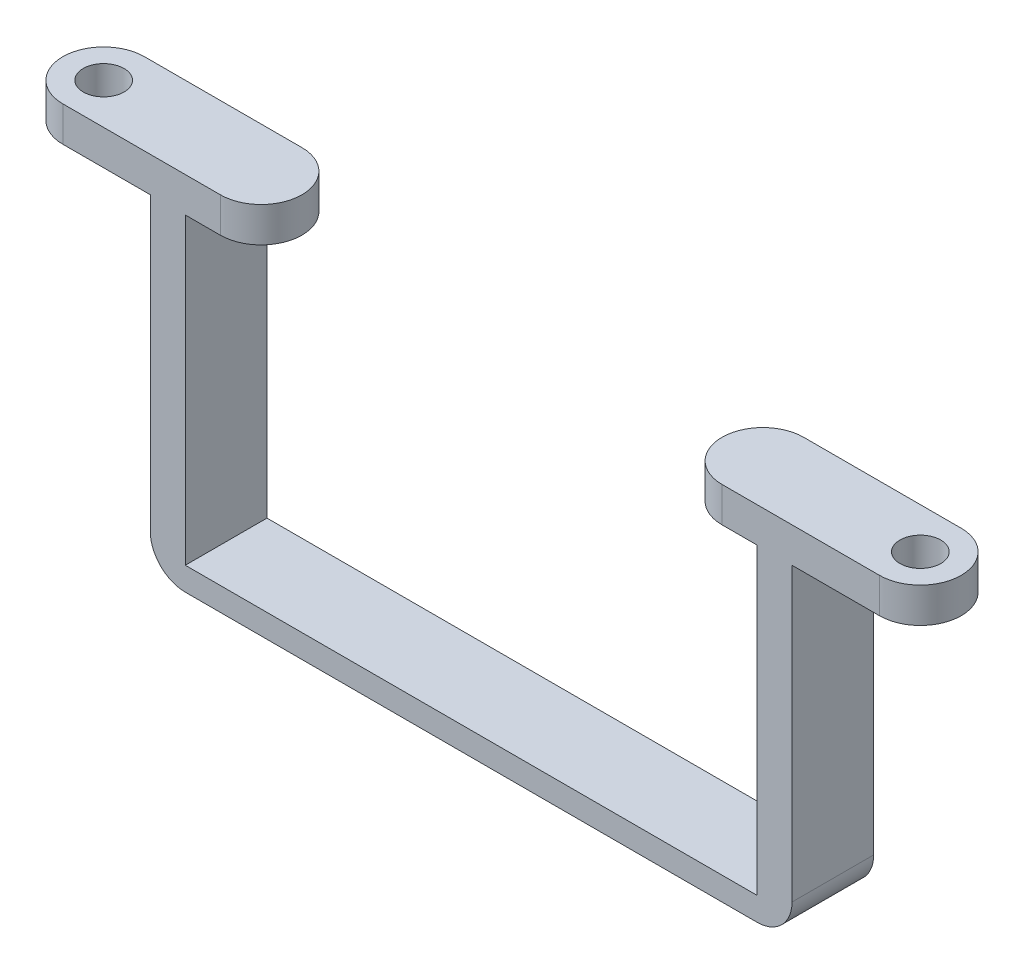
SolidWorks part; units mm, degrees
ref_plane "Front Plane" through (0, 0, 0) normal (0, 0, 1) x (1, 0, 0)
ref_plane "Top Plane" through (0, 0, 0) normal (0, 1, 0) x (1, 0, 0)
ref_plane "Right Plane" through (0, 0, 0) normal (1, 0, 0) x (0, 0, -1)
sketch "Sketch1" plane through (0, 0, 0) normal (0, 1, 0) x (1, 0, 0)
  line L0 (0, 3.5) -> (10.5, 3.5)
  line L2 (10.5, -3.5) -> (0, -3.5)
  line L3 (10.5, 3.5) -> (13.5, 3.5)
  line L4 (10.5, -3.5) -> (13.5, -3.5)
  circle A0 centre (0, 0) radius 1.75
  arc A1 (0, 3.5) -> (0, -3.5) centre (0, 0) ccw
  arc A2 (13.5, -3.5) -> (13.5, 3.5) centre (13.5, 0) ccw
  dimension "D1" = 3.5
  dimension "D2" = 10.5
  dimension "D3" = 7
  dimension "D4" = 3
extrude "Boss-Extrude1" add sketch "Sketch1" along normal blind 3
sketch "Sketch2" plane through (0, 0, 0) normal (0, 1, 0) x (1, 0, 0)
  line L0 (10.5, 3.5) -> (7.5, 3.5)
  line L1 (13.5, 3.5) -> (0, 3.5) construction
  line L2 (7.5, 3.5) -> (7.5, -3.5)
  line L3 (0, -3.5) -> (13.5, -3.5) construction
  line L4 (7.5, -3.5) -> (10.5, -3.5)
  line L5 (10.5, -3.5) -> (10.5, 3.5)
  line L6 (13.5, 3.5) -> (0, 3.5) construction
  dimension "D1" = 3
extrude "Boss-Extrude2" add sketch "Sketch2" against normal offset from surface (26 mm away) 1
sketch "Sketch3" plane through (0, -26, 0) normal (0, -1, 0) x (1, 0, 0)
  line L0 (7.5, 3.5) -> (7.5, -3.5)
  line L1 (7.5, -3.5) -> (35, -3.5)
  line L2 (35, -3.5) -> (35, 3.5)
  line L3 (35, 3.5) -> (7.5, 3.5)
  line L4 (35, 39.31) -> (35, -38.31) construction
  line L7 (70.4939, -38.31) -> (-0.4939, -38.31) construction
extrude "Boss-Extrude3" add sketch "Sketch3" along normal blind 2
fillet "Fillet1" radius 3 1 edges at (7.5, -28, 0)
mirror "Mirror1" about plane through (35, -28, -3.5) normal (-1, 0, 0) of bodies 103
